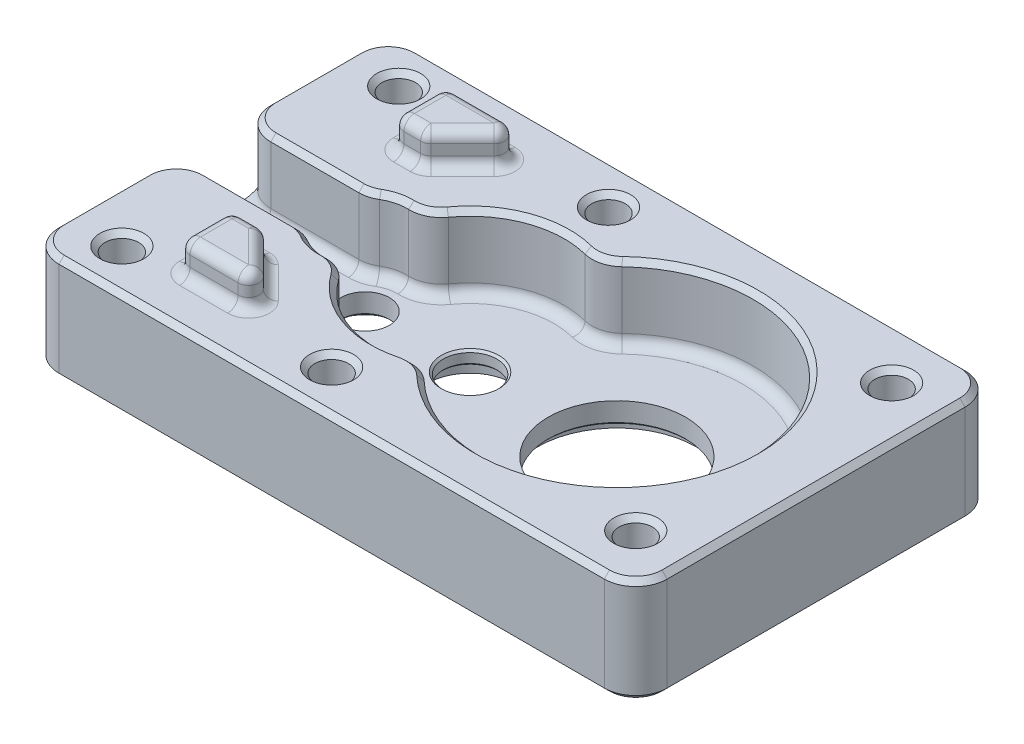
SolidWorks part; units mm, degrees
ref_plane "Front Plane" through (0, 0, 0) normal (0, 0, 1) x (1, 0, 0)
ref_plane "Top Plane" through (0, 0, 0) normal (0, 1, 0) x (1, 0, 0)
ref_plane "Right Plane" through (0, 0, 0) normal (1, 0, 0) x (0, 0, -1)
sketch "Sketch1" plane through (0, 28, 0) normal (0, 1, 0) x (1, 0, 0)
  line L1 (43, -17.2) -> (-15, -17.2)
  line L2 (43, -17.2) -> (43, 17.2)
  line L3 (43, 17.2) -> (-15, 17.2)
  line L4 (-15, -17.2) -> (-15, 17.2)
  circle A0 centre (0, 0) radius 14 construction
  circle A1 centre (0, 0) radius 2.5 construction
  circle A2 centre (10, 0) radius 7.5 construction
  circle A3 centre (10, 0) radius 2.5 construction
  circle A4 centre (24, 0) radius 11.5 construction
  circle A5 centre (24, 0) radius 3 construction
  circle A6 centre (24, 0) radius 6.5 construction
  point P4 (-15, 0)
  dimension "D4" = 28
  dimension "D5" = 5
  dimension "D6" = 15
  dimension "D7" = 5
  dimension "D8" = 23
  dimension "D9" = 6
  dimension "D10" = 13
  dimension "D1" = 34.4
  dimension "D2" = 58
  dimension "D3" = 15
extrude "Boss-Extrude1" add sketch "Sketch1" along normal blind 3 contours L4 L3 L2 L1
sketch "Sketch2" plane through (0, 28, 0) normal (0, -1, 0) x (1, 0, 0)
  circle A0 centre (0, 0) radius 3.85
  dimension "D1" = 7.7
extrude "Cut-Extrude1" cut sketch "Sketch2" against normal blind 1
sketch "Sketch3" plane through (0, 29, 0) normal (0, -1, 0) x (1, 0, 0)
  circle A0 centre (0, 0) radius 2.3
  dimension "D1" = 4.6
extrude "Cut-Extrude2" cut sketch "Sketch3" against normal through all
sketch "Sketch4" plane through (0, 31, 0) normal (0, 1, 0) x (1, 0, 0)
  line L4 (-15, -17.2) -> (43, -17.2)
  line L5 (43, -17.2) -> (43, 17.2)
  line L6 (43, 17.2) -> (-15, 17.2)
  line L7 (-15, 17.2) -> (-15, -17.2)
  line L8 (-15, -17.2) -> (43, -17.2)
  line L9 (43, -17.2) -> (43, 17.2)
  line L10 (43, 17.2) -> (-15, 17.2)
  line L11 (-15, 17.2) -> (-15, -17.2)
  arc A0 (1.75, 3.5969) -> (1.75, -3.5969) centre (0, 0) ccw
  arc A1 (1.75, -3.5969) -> (13.8571, -8.1316) centre (10, 0) ccw
  arc A2 (13.8571, -8.1316) -> (13.8571, 8.1316) centre (24, 0) ccw
  arc A3 (13.8571, 8.1316) -> (1.75, 3.5969) centre (10, 0) ccw
  dimension "D1" = 8
  dimension "D2" = 18
  dimension "D3" = 26
  dimension "D4" = 0
extrude "Boss-Extrude2" add sketch "Sketch4" along normal blind 7
sketch "Sketch5" plane through (0, 38, 0) normal (0, 1, 0) x (1, 0, 0)
  line L0 (-2.6458, 3) -> (-2.6458, -3)
  line L1 (-2.6458, 3) -> (-15, 3)
  line L2 (-2.6458, -3) -> (-15, -3)
  line L3 (-15, 3) -> (-15, -3)
  line L4 (-15, -17.2) -> (-15, 17.2) construction
  arc A0 (1.75, 3.5969) -> (1.75, -3.5969) centre (0, 0) ccw construction
  dimension "D1" = 6
extrude "Cut-Extrude3" cut sketch "Sketch5" against normal blind 7
sketch "Sketch6" plane through (0, 28, 0) normal (0, -1, 0) x (1, 0, 0)
  circle A0 centre (10, 0) radius 4.1
  dimension "D1" = 8.2
extrude "Cut-Extrude4" cut sketch "Sketch6" against normal blind 1.7
sketch "Sketch7" plane through (0, 29.7, 0) normal (0, -1, 0) x (1, 0, 0)
  circle A0 centre (10, 0) radius 2.55
  circle A1 centre (10, 0) radius 4.1 construction
  dimension "D1" = 5.1
extrude "Cut-Extrude5" cut sketch "Sketch7" against normal through all
sketch "Sketch8" plane through (0, 28, 0) normal (0, -1, 0) x (1, 0, 0)
  circle A0 centre (24, 0) radius 7.6
  dimension "D1" = 15.2
extrude "Cut-Extrude6" cut sketch "Sketch8" against normal blind 1
sketch "Sketch9" plane through (0, 29, 0) normal (0, -1, 0) x (1, 0, 0)
  circle A0 centre (24, 0) radius 6.55
  dimension "D1" = 13.1
extrude "Cut-Extrude7" cut sketch "Sketch9" against normal through all
fillet "Fillet1" radius 3 4 edges at (-15, 33, 17.2) (43, 33, 17.2) (43, 33, -17.2) (-15, 33, -17.2)
fillet "Fillet2" radius 3 8 edges at (13.8571, 34.5, 8.1316) (1.75, 34.5, 3.5969) (-2.6458, 34.5, 3) (-2.6458, 34.5, -3) (13.8571, 34.5, -8.1316) (1.75, 34.5, -3.5969) (-15, 34.5, 3) (-15, 34.5, -3)
fillet "Fillet3" radius 1 15 edges at (-14.1213, 31, 3.8787) (-7.8028, 31, 3) (-2.8038, 31, 3.1091) (-1, 31, 3.873) (1.572, 31, 4.3025) (6.9319, 31, 8.4609) (13.75, 31, 8.7142) (37, 31, 0) (13.75, 31, -8.7142) (6.9319, 31, -8.4609) (1.572, 31, -4.3025) (-1, 31, -3.873) (-2.8038, 31, -3.1091) (-14.1213, 31, -3.8787) (-7.8028, 31, -3)
chamfer "Chamfer1" distance 0.2 angle 45 4 edges at (10, 29.7, -2.55) (10, 31, -2.55) (0, 29, -2.3) (24, 29, -6.55)
sketch "Sketch10" plane through (0, 28, 0) normal (0, -1, 0) x (1, 0, 0)
  circle A0 centre (-10, -13.2) radius 1.6
  circle A1 centre (-10, -13.2) radius 2.1 construction
  circle A2 centre (10, -13.2) radius 1.6
  circle A3 centre (-10, 13.2) radius 1.6
  circle A4 centre (10, 13.2) radius 1.6
  circle A5 centre (10, 13.2) radius 2.1 construction
  dimension "D1" = 3.2
extrude "Cut-Extrude8" cut sketch "Sketch10" against normal through all
sketch "Sketch11" plane through (0, 28, 0) normal (0, -1, 0) x (1, 0, 0)
  line L0 (40, -17.2) -> (-12, -17.2) construction
  line L1 (43, 14.2) -> (43, -14.2) construction
  circle A0 centre (38, -12.2) radius 1.6
  dimension "D1" = 3.2
  dimension "D2" = 5
  dimension "D3" = 5
extrude "Cut-Extrude9" cut sketch "Sketch11" against normal through all
sketch "Sketch12" plane through (0, 28, 0) normal (0, -1, 0) x (1, 0, 0)
  circle A0 centre (38, -12.2) radius 2.1
  dimension "D1" = 4.2
extrude "Cut-Extrude10" cut sketch "Sketch12" against normal blind 5
mirror "Mirror1" about plane through (0, 0, 0) normal (0, 0, 1) of "Cut-Extrude10", "Cut-Extrude9"
sketch "Sketch13" plane through (0, 38, 0) normal (0, 1, 0) x (1, 0, 0)
  line L0 (3, -12.7) -> (-5, -12.7)
  line L1 (-5, -12.7) -> (-5, -7.7)
  line L2 (-5, -7.7) -> (-2, -7.7)
  line L3 (-2, -7.7) -> (3, -12.7)
  line L4 (-12, -17.2) -> (40, -17.2) construction
  line L5 (-15, -6) -> (-15, -14.2) construction
  dimension "D1" = 45
  dimension "D2" = 4.5
  dimension "D3" = 10
  dimension "D4" = 8
  dimension "D5" = 5
extrude "Boss-Extrude3" add sketch "Sketch13" along normal blind 3
fillet "Fillet4" radius 1 8 edges at (-1, 41, 12.7) (-5, 41, 10.2) (-3.5, 41, 7.7) (0.5, 41, 10.2) (-2, 39.5, 7.7) (-5, 39.5, 7.7) (-5, 39.5, 12.7) (3, 39.5, 12.7)
fillet "Fillet5" radius 1 8 edges at (-4.7071, 38, 12.4071) (-5, 38, 10.2) (-4.7071, 38, 7.9929) (-3.2071, 38, 7.7) (-2.0315, 38, 7.7761) (-0.2071, 38, 9.4929) (1.5097, 38, 12.0827) (-1.7071, 38, 12.7)
mirror "Mirror2" about plane through (0, 0, 0) normal (0, 0, 1) of "Fillet5", "Fillet4", "Boss-Extrude3"
chamfer "Chamfer2" distance 0.5 angle 45 44 edges at (38, 28, 14.3) (38, 28, -14.3) (-10, 28, 11.6) (10, 28, 11.6) (10, 28, -14.8) (-10, 28, -14.8) (14, 28, 17.2) (42.1213, 28, 16.3213) (-14.1213, 28, 16.3213) (43, 28, 0) (-15, 28, 0) (42.1213, 28, -16.3213) (-14.1213, 28, -16.3213) (14, 28, -17.2) (-10, 38, 11.6) (10, 38, 11.6) (38, 38, 13.8) (38, 38, -13.8) (10, 38, -14.8) (-10, 38, -14.8) (-7.8028, 38, 3) (-2.8038, 38, 3.1091) (-14.1213, 38, 3.8787) (-1, 38, 3.873) (-15, 38, 10.1) (1.572, 38, 4.3025) (-14.1213, 38, 16.3213) (6.9319, 38, 8.4609) (14, 38, 17.2) (13.75, 38, 8.7142) (42.1213, 38, 16.3213) (37, 38, 0) (43, 38, 0) (13.75, 38, -8.7142) (42.1213, 38, -16.3213) (6.9319, 38, -8.4609) (14, 38, -17.2) (1.572, 38, -4.3025) (-14.1213, 38, -16.3213) (-1, 38, -3.873) (-15, 38, -10.1) (-2.8038, 38, -3.1091) (-14.1213, 38, -3.8787) (-7.8028, 38, -3)
